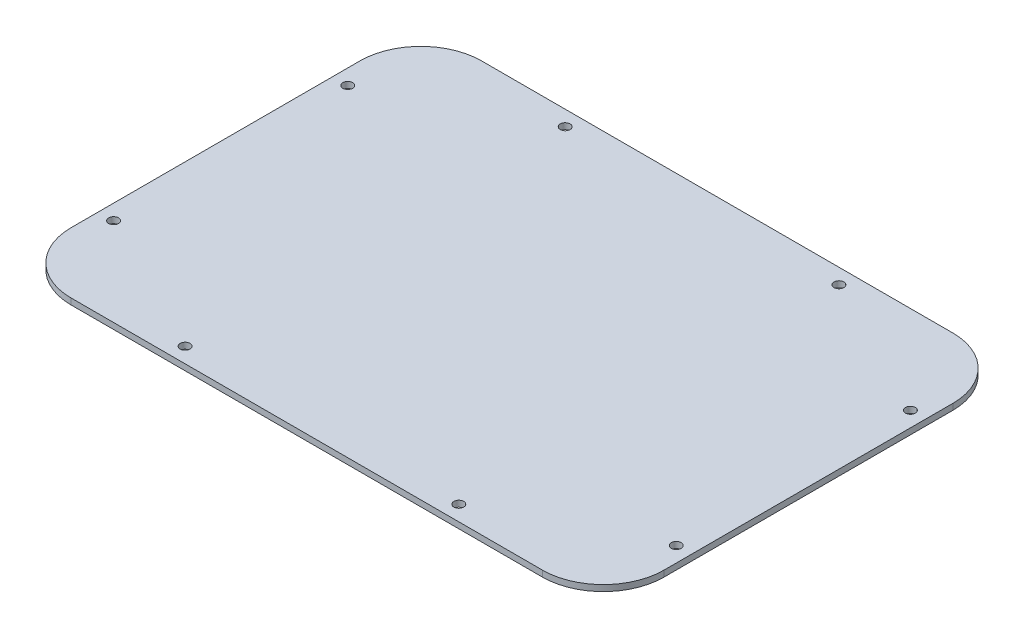
SolidWorks part; units mm, degrees
ref_plane "前视基准面" through (0, 0, 0) normal (0, 0, 1) x (1, 0, 0)
ref_plane "上视基准面" through (0, 0, 0) normal (0, 1, 0) x (1, 0, 0)
ref_plane "右视基准面" through (0, 0, 0) normal (1, 0, 0) x (0, 0, -1)
sketch "草图1" plane through (0, 0, 0) normal (0, 1, 0) x (1, 0, 0)
  line L1 (-195, 135) -> (195, 135)
  line L2 (-195, 135) -> (-195, -135)
  line L3 (-195, -135) -> (195, -135)
  line L4 (195, 135) -> (195, -135)
  line L5 (-195, 135) -> (195, -135) construction
  line L6 (-195, -135) -> (195, 135) construction
  point P0 (0, 0)
  dimension "D1" = 390
  dimension "D2" = 270
extrude "凸台-拉伸1" add sketch "草图1" along normal blind 4
fillet "圆角1" radius 40 4 edges at (-195, 2, -135) (-195, 2, 135) (195, 2, 135) (195, 2, -135)
sketch "草图2" plane through (0, 4, 0) normal (0, 1, 0) x (1, 0, 0)
  circle A0 centre (-185, -77) radius 3.25
  circle A1 centre (-185, 77) radius 3.25
  circle A2 centre (-90, 125) radius 3.25
  circle A3 centre (-90, -125) radius 3.25
  circle A4 centre (90, -125) radius 3.25
  circle A5 centre (185, -77) radius 3.25
  circle A6 centre (185, 77) radius 3.25
  circle A7 centre (90, 125) radius 3.25
  dimension "D1" = 6.5
extrude "切除-拉伸1" cut sketch "草图2" against normal through all
